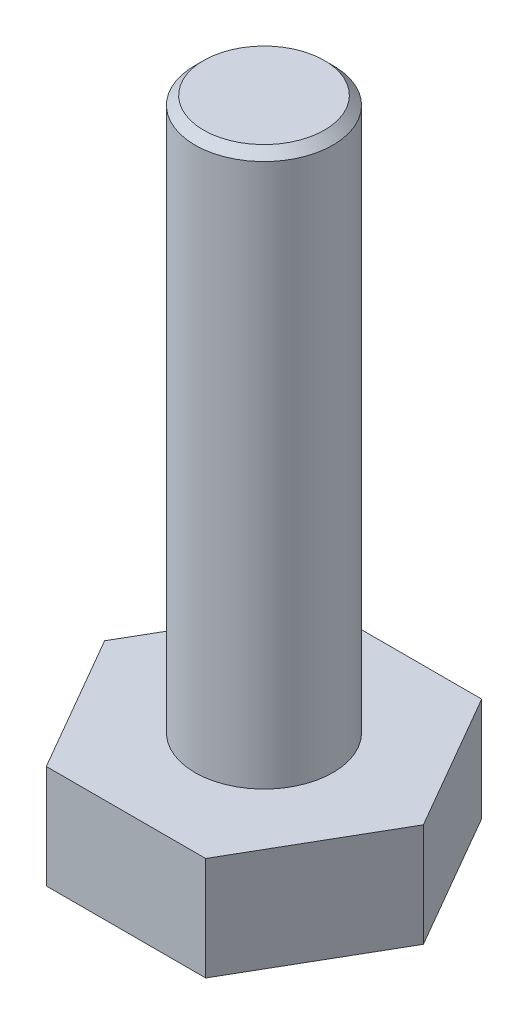
SolidWorks part; units mm, degrees
ref_plane "Front Plane" through (0, 0, 0) normal (0, 0, 1) x (1, 0, 0)
ref_plane "Top Plane" through (0, 0, 0) normal (0, 1, 0) x (1, 0, 0)
ref_plane "Right Plane" through (0, 0, 0) normal (1, 0, 0) x (0, 0, -1)
sketch "Sketch1" plane through (0, 0, 0) normal (0, 1, 0) x (1, 0, 0)
  line L1 (4.6188, 0) -> (2.3094, 4)
  line L2 (2.3094, 4) -> (-2.3094, 4)
  line L3 (-2.3094, 4) -> (-4.6188, 0)
  line L4 (-4.6188, 0) -> (-2.3094, -4)
  line L5 (-2.3094, -4) -> (2.3094, -4)
  line L6 (2.3094, -4) -> (4.6188, 0)
  circle A0 centre (0, 0) radius 4 construction
  dimension "D1" = 8
extrude "Boss-Extrude1" add sketch "Sketch1" against normal blind 3
sketch "Sketch2" plane through (0, 0, 0) normal (0, 1, 0) x (1, 0, 0)
  circle A0 centre (0, 0) radius 2
  dimension "D1" = 4
extrude "Boss-Extrude2" add sketch "Sketch2" along normal blind 16
chamfer "Chamfer1" distance 0.25 angle 45 1 edges at (0, 16, 2)
